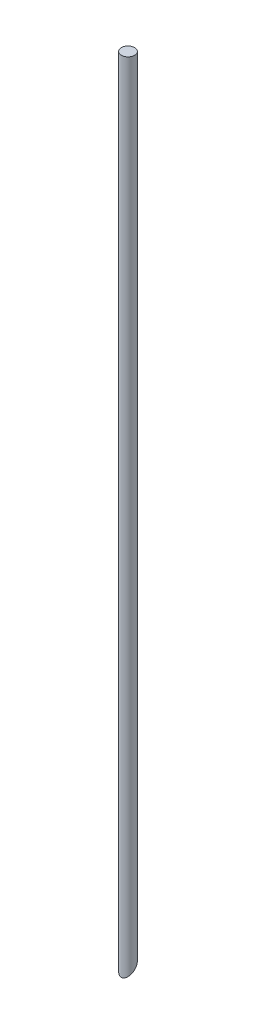
SolidWorks part; units mm, degrees
ref_plane "前视基准面" through (0, 0, 0) normal (0, 0, 1) x (1, 0, 0)
ref_plane "上视基准面" through (0, 0, 0) normal (0, 1, 0) x (1, 0, 0)
ref_plane "右视基准面" through (0, 0, 0) normal (1, 0, 0) x (0, 0, -1)
sketch "草图1" plane through (0, 0, 0) normal (0, 1, 0) x (1, 0, 0)
  circle A0 centre (0, 0) radius 5
  dimension "D1" = 10
extrude "凸台-拉伸1" add sketch "草图1" along normal blind 600
sketch "草图2" plane through (0, 0, 0) normal (1, 0, 0) x (0, 0, -1)
  line L0 (-5, 0) -> (5, 10)
  line L1 (5, 0) -> (5, 600) construction
  line L2 (-5, 0) -> (5, 0) construction
  line L3 (5, 10) -> (5, 0)
  line L4 (5, 0) -> (-5, 0)
  dimension "D1" = 45
extrude "切除-拉伸1" cut sketch "草图2" against normal through all both and the other way through all
